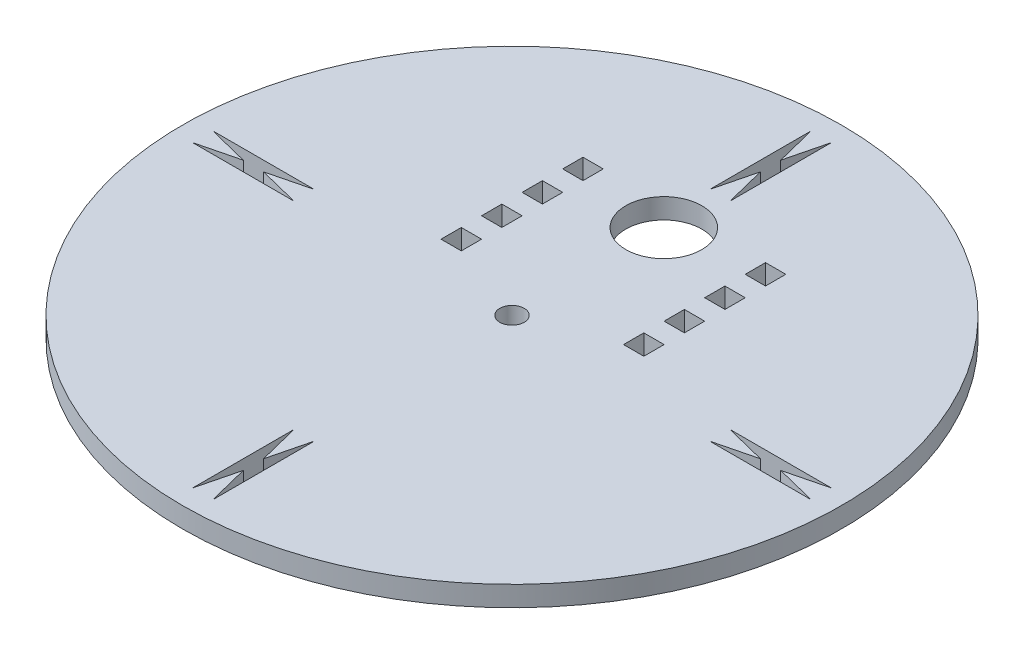
SolidWorks part; units mm, degrees
ref_plane "Front Plane" through (0, 0, 0) normal (0, 0, 1) x (1, 0, 0)
ref_plane "Top Plane" through (0, 0, 0) normal (0, 1, 0) x (1, 0, 0)
ref_plane "Right Plane" through (0, 0, 0) normal (1, 0, 0) x (0, 0, -1)
sketch "Sketch1" plane through (0, 0, 0) normal (0, 1, 0) x (1, 0, 0)
  line L0 (-62.9674, 163.9506) -> (-62.9674, -1.1494) construction
  line L1 (-145.5174, 81.4006) -> (19.5826, 81.4006) construction
  line L2 (-37.5674, 188.935) -> (-37.5674, -106.0892) construction
  line L3 (-173.8413, 106.8006) -> (52.6322, 106.8006) construction
  line L4 (-150.5974, 132.2006) -> (24.6626, 132.2006) construction
  line L5 (-88.3674, 188.935) -> (-88.3674, -106.0892) construction
  line L6 (-83.2874, 114.4206) -> (-83.2874, 109.3406)
  line L7 (-88.3674, 89.0206) -> (-83.2874, 89.0206)
  line L8 (-88.3674, 89.0206) -> (-88.3674, 94.1006)
  line L9 (-88.3674, 94.1006) -> (-83.2874, 94.1006)
  line L10 (-83.2874, 89.0206) -> (-83.2874, 94.1006)
  line L11 (-88.3674, 99.1806) -> (-83.2874, 99.1806)
  line L12 (-88.3674, 99.1806) -> (-88.3674, 104.2606)
  line L13 (-88.3674, 104.2606) -> (-83.2874, 104.2606)
  line L14 (-83.2874, 99.1806) -> (-83.2874, 104.2606)
  line L15 (-88.3674, 109.3406) -> (-83.2874, 109.3406)
  line L16 (-88.3674, 114.4206) -> (-88.3674, 109.3406)
  line L17 (-88.3674, 114.4206) -> (-83.2874, 114.4206)
  line L18 (-83.2874, 124.5806) -> (-83.2874, 119.5006)
  line L19 (-88.3674, 119.5006) -> (-83.2874, 119.5006)
  line L20 (-88.3674, 124.5806) -> (-88.3674, 119.5006)
  line L21 (-88.3674, 124.5806) -> (-83.2874, 124.5806)
  line L22 (-37.5674, 124.5806) -> (-42.6474, 124.5806)
  line L23 (-37.5674, 124.5806) -> (-37.5674, 119.5006)
  line L24 (-37.5674, 119.5006) -> (-42.6474, 119.5006)
  line L25 (-42.6474, 124.5806) -> (-42.6474, 119.5006)
  line L26 (-37.5674, 114.4206) -> (-42.6474, 114.4206)
  line L27 (-37.5674, 114.4206) -> (-37.5674, 109.3406)
  line L28 (-37.5674, 109.3406) -> (-42.6474, 109.3406)
  line L29 (-42.6474, 99.1806) -> (-42.6474, 104.2606)
  line L30 (-37.5674, 104.2606) -> (-42.6474, 104.2606)
  line L31 (-37.5674, 99.1806) -> (-37.5674, 104.2606)
  line L32 (-37.5674, 99.1806) -> (-42.6474, 99.1806)
  line L33 (-42.6474, 89.0206) -> (-42.6474, 94.1006)
  line L34 (-37.5674, 94.1006) -> (-42.6474, 94.1006)
  line L35 (-37.5674, 89.0206) -> (-37.5674, 94.1006)
  line L36 (-37.5674, 89.0206) -> (-42.6474, 89.0206)
  line L37 (-42.6474, 114.4206) -> (-42.6474, 109.3406)
  circle A0 centre (-62.9674, 81.4006) radius 82.55
  circle A1 centre (-62.9674, 81.4006) radius 3.048
  circle A2 centre (-62.9674, 119.4321) radius 9.525
  dimension "D1" = 165.1
  dimension "D12" = 6.096
  dimension "D13" = 38.0314
  dimension "D14" = 19.05
  dimension "D2" = 25.4
  dimension "D3" = 25.4
  dimension "D4" = 25.4
  dimension "D5" = 25.4
  dimension "D6" = 5.08
  dimension "D7" = 5.08
  dimension "D8" = 5.08
  dimension "D9" = 5.08
  dimension "D10" = 5.08
  dimension "D11" = 2.54
extrude "Boss-Extrude1" add sketch "Sketch1" along normal blind 5.08
sketch "Sketch2" plane through (0, 5.08, 0) normal (0, 1, 0) x (1, 0, 0)
  line L0 (-62.9674, -1.1494) -> (-62.9674, 163.9506) construction
  line L1 (-145.5174, 81.4006) -> (19.5826, 81.4006) construction
  line L2 (-62.9674, 148.7106) -> (-60.4274, 158.8706)
  line L3 (-60.4274, 158.8706) -> (-60.4274, 133.4706)
  line L4 (-60.4274, 133.4706) -> (-62.9674, 143.6306)
  line L5 (-65.5074, 133.4706) -> (-62.9674, 143.6306)
  line L6 (-65.5074, 158.8706) -> (-65.5074, 133.4706)
  line L7 (-62.9674, 148.7106) -> (-65.5074, 158.8706)
  line L8 (4.3426, 81.4006) -> (14.5026, 78.8606)
  line L9 (14.5026, 78.8606) -> (-10.8974, 78.8606)
  line L10 (-10.8974, 78.8606) -> (-0.7374, 81.4006)
  line L11 (-10.8974, 83.9406) -> (-0.7374, 81.4006)
  line L12 (14.5026, 83.9406) -> (-10.8974, 83.9406)
  line L13 (4.3426, 81.4006) -> (14.5026, 83.9406)
  line L14 (-62.9674, 14.0906) -> (-65.5074, 3.9306)
  line L15 (-65.5074, 3.9306) -> (-65.5074, 29.3306)
  line L16 (-65.5074, 29.3306) -> (-62.9674, 19.1706)
  line L17 (-60.4274, 29.3306) -> (-62.9674, 19.1706)
  line L18 (-60.4274, 3.9306) -> (-60.4274, 29.3306)
  line L19 (-62.9674, 14.0906) -> (-60.4274, 3.9306)
  line L20 (-130.2774, 81.4006) -> (-140.4374, 83.9406)
  line L21 (-140.4374, 83.9406) -> (-115.0374, 83.9406)
  line L22 (-115.0374, 83.9406) -> (-125.1974, 81.4006)
  line L23 (-115.0374, 78.8606) -> (-125.1974, 81.4006)
  line L24 (-140.4374, 78.8606) -> (-115.0374, 78.8606)
  line L25 (-130.2774, 81.4006) -> (-140.4374, 78.8606)
  circle A0 centre (-62.9674, 81.4006) radius 82.55 construction
  point P13 (-62.9674, 81.4006)
  point P35 (-60.4274, 78.8606)
  point P36 (-62.9674, 81.4006)
  dimension "D1" = 2.54
  dimension "D2" = 10.16
  dimension "D3" = 10.16
  dimension "D4" = 25.4
  dimension "D5" = 5.08
  dimension "D6" = 4
extrude "Cut-Extrude1" cut sketch "Sketch2" against normal blind 5.08
